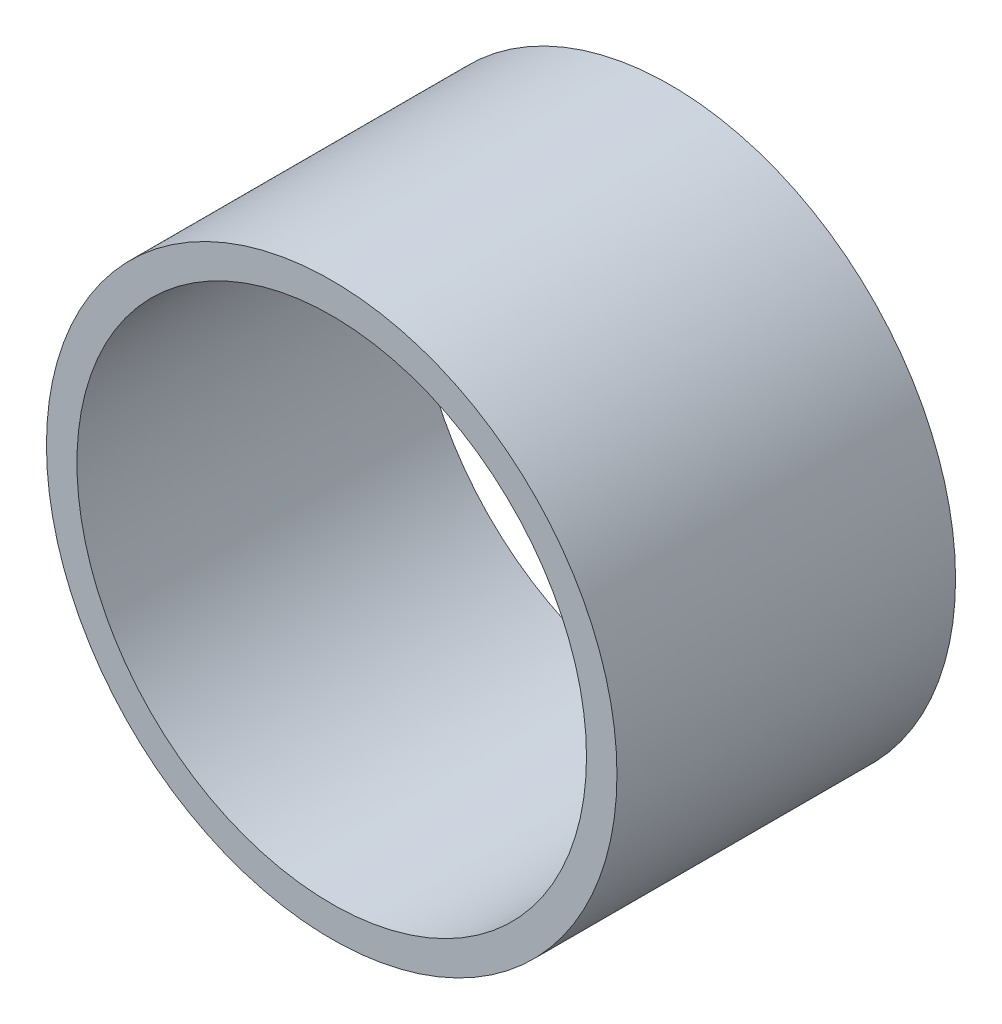
SolidWorks part; units mm, degrees
ref_plane "Front Plane" through (0, 0, 0) normal (0, 0, 1) x (1, 0, 0)
ref_plane "Top Plane" through (0, 0, 0) normal (0, 1, 0) x (1, 0, 0)
ref_plane "Right Plane" through (0, 0, 0) normal (1, 0, 0) x (0, 0, -1)
sketch "Sketch1" plane through (0, 0, 0) normal (0, 0, 1) x (1, 0, 0)
  circle A0 centre (0, 0) radius 15
  circle A1 centre (0, 0) radius 17
  dimension "D1" = 30
  dimension "D2" = 2
extrude "Boss-Extrude1" add sketch "Sketch1" along normal blind 20
other "Move Face1" face at (17, 0, 20) parameters "D1"=0.15
other "Move Face2" face at (15, 0, 20) parameters "D1"=0.05
